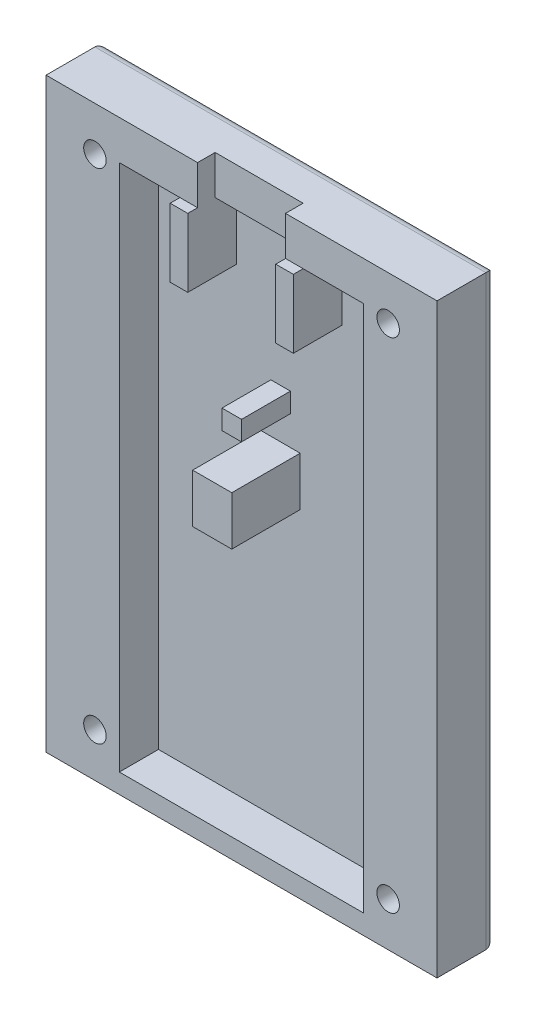
SolidWorks part; units mm, degrees
ref_plane "Front Plane" through (0, 0, 0) normal (1, 0, 0) x (0, 1, 0)
ref_plane "Top Plane" through (0, 0, 0) normal (0, 0, 1) x (0, 1, 0)
ref_plane "Right Plane" through (0, 0, 0) normal (0, 1, 0) x (-1, 0, 0)
sketch "Sketch1" plane through (0, 0, 0) normal (0, 0, 1) x (0, 1, 0)
  line L0 (0, -20) -> (60, -20) construction
  line L1 (0, 0) -> (60, 0)
  line L2 (0, 0) -> (0, -40)
  line L3 (0, -40) -> (60, -40)
  line L4 (60, 0) -> (60, -40)
  dimension "D1" = 60
  dimension "D2" = 40
extrude "Boss-Extrude1" add sketch "Sketch1" along normal blind 6
sketch "Sketch3" plane through (0, 0, 6) normal (0, 0, 1) x (1, 0, 0)
  line L0 (0, 55.5) -> (40, 55.5) construction
  line L1 (0, 60) -> (0, 0) construction
  line L2 (40, 0) -> (40, 60) construction
  line L3 (0, 4.5) -> (40, 4.5) construction
  line L4 (0, 30) -> (40, 30) construction
  line L5 (20, 60) -> (20, 0) construction
  line L6 (40, 60) -> (0, 60) construction
  line L7 (0, 0) -> (40, 0) construction
  circle A0 centre (5, 4.5) radius 1.15
  circle A1 centre (35, 4.5) radius 1.15
  circle A2 centre (5, 55.5) radius 1.15
  circle A3 centre (35, 55.5) radius 1.15
  dimension "D5" = 2.3
  dimension "D6" = 2.3
  dimension "D7" = 2.3
  dimension "D8" = 2.3
  dimension "D1" = 25.5
  dimension "D2" = 25.5
  dimension "D3" = 15
  dimension "D4" = 15
  dimension "D9" = 15
  dimension "D10" = 15
extrude "Cut-Extrude2" cut sketch "Sketch3" against normal through all
sketch "Sketch12" plane through (0, 0, 6) normal (0, 0, 1) x (1, 0, 0)
  line L0 (20, 60) -> (20, 0) construction
  line L1 (40, 60) -> (0, 60) construction
  line L2 (0, 0) -> (40, 0) construction
  line L4 (32.5, 56) -> (7.5, 56)
  line L5 (32.5, 56) -> (32.5, 2)
  line L6 (32.5, 2) -> (7.5, 2)
  line L7 (7.5, 56) -> (7.5, 2)
  line L8 (32.5, 56) -> (7.5, 2) construction
  line L9 (32.5, 2) -> (7.5, 56) construction
  point P6 (20, 29)
  dimension "D1" = 2
  dimension "D2" = 25
  dimension "D3" = 4
extrude "Cut-Extrude10" cut sketch "Sketch12" against normal blind 4
sketch "Sketch13" plane through (0, 0, 0) normal (0, 0, -1) x (1, 0, 0)
  line L0 (5, -4.5) -> (35, -4.5) construction
  line L1 (5, -55.5) -> (35, -55.5) construction
  line L3 (7.4249, -55.5) -> (6.2124, -53.4)
  line L4 (6.2124, -53.4) -> (3.7876, -53.4)
  line L5 (3.7876, -53.4) -> (2.5751, -55.5)
  line L6 (2.5751, -55.5) -> (3.7876, -57.6)
  line L7 (3.7876, -57.6) -> (6.2124, -57.6)
  line L8 (6.2124, -57.6) -> (7.4249, -55.5)
  line L9 (32.5751, -55.5) -> (33.7876, -57.6)
  line L10 (33.7876, -57.6) -> (36.2124, -57.6)
  line L11 (36.2124, -57.6) -> (37.4249, -55.5)
  line L12 (37.4249, -55.5) -> (36.2124, -53.4)
  line L13 (36.2124, -53.4) -> (33.7876, -53.4)
  line L14 (33.7876, -53.4) -> (32.5751, -55.5)
  line L15 (7.4249, -4.5) -> (6.2124, -2.4)
  line L16 (6.2124, -2.4) -> (3.7876, -2.4)
  line L17 (3.7876, -2.4) -> (2.5751, -4.5)
  line L18 (2.5751, -4.5) -> (3.7876, -6.6)
  line L19 (3.7876, -6.6) -> (6.2124, -6.6)
  line L20 (6.2124, -6.6) -> (7.4249, -4.5)
  line L21 (32.5751, -4.5) -> (33.7876, -6.6)
  line L22 (33.7876, -6.6) -> (36.2124, -6.6)
  line L23 (36.2124, -6.6) -> (37.4249, -4.5)
  line L24 (37.4249, -4.5) -> (36.2124, -2.4)
  line L25 (36.2124, -2.4) -> (33.7876, -2.4)
  line L26 (33.7876, -2.4) -> (32.5751, -4.5)
  circle A0 centre (5, -55.5) radius 2.1 construction
  circle A1 centre (35, -55.5) radius 2.1 construction
  circle A2 centre (5, -4.5) radius 2.1 construction
  circle A3 centre (35, -4.5) radius 2.1 construction
  dimension "D1" = 4.2
  dimension "D2" = 4.2
  dimension "D3" = 4.2
  dimension "D4" = 4.2
extrude "Cut-Extrude11" cut sketch "Sketch13" against normal blind 2.8
fillet "Fillet1" radius 1 4 edges at (40, 30, 0) (20, 0, 0) (0, 30, 0) (20, 60, 0)
sketch "Sketch15" plane through (0, 0, 6) normal (0, 0, 1) x (1, 0, 0)
  line L0 (20, 60) -> (20, 56) construction
  line L1 (40, 60) -> (0, 60) construction
  line L2 (32.5, 56) -> (7.5, 56) construction
  line L3 (32.5, 56) -> (7.5, 56) construction
  line L4 (24.5, 56) -> (15.5, 56)
  line L5 (24.5, 56) -> (24.5, 60)
  line L6 (24.5, 60) -> (15.5, 60)
  line L7 (15.5, 56) -> (15.5, 60)
  line L8 (24.5, 56) -> (15.5, 60) construction
  line L9 (24.5, 60) -> (15.5, 56) construction
  point P6 (20, 58)
  dimension "D1" = 9
extrude "Cut-Extrude13" cut sketch "Sketch15" against normal blind 1.8
sketch "Sketch16" plane through (0, 0, 2) normal (0, 0, 1) x (1, 0, 0)
  line L0 (20, 56) -> (20, 2) construction
  line L1 (32.5, 56) -> (7.5, 56) construction
  line L2 (7.5, 2) -> (32.5, 2) construction
  line L3 (18, 30.5) -> (18, 35.5)
  line L4 (18, 30.5) -> (22, 30.5)
  line L5 (18, 35.5) -> (22, 35.5)
  line L6 (22, 30.5) -> (22, 35.5)
  line L7 (18, 30.5) -> (22, 35.5) construction
  line L8 (18, 35.5) -> (22, 30.5) construction
  line L9 (0, 0) -> (40, 0) construction
  point P7 (20, 33)
  point P9 (20, 35.5)
  point P14 (22, 33)
  dimension "D1" = 35.5
  dimension "D2" = 5
  dimension "D3" = 4
extrude "Boss-Extrude2" add sketch "Sketch16" along normal blind 7
sketch "Sketch17" plane through (0, 0, 2) normal (0, 0, 1) x (1, 0, 0)
  line L0 (20, 56) -> (20, 35.5) construction
  line L1 (15.5, 56) -> (24.5, 56) construction
  line L2 (22, 35.5) -> (18, 35.5) construction
  line L3 (21, 38.5) -> (21, 40.5)
  line L4 (21, 38.5) -> (19, 38.5)
  line L5 (21, 40.5) -> (19, 40.5)
  line L6 (19, 38.5) -> (19, 40.5)
  line L7 (21, 38.5) -> (19, 40.5) construction
  line L8 (21, 40.5) -> (19, 38.5) construction
  line L10 (15.5, 56) -> (13.7, 56)
  line L11 (15.5, 56) -> (15.5, 49)
  line L12 (15.5, 49) -> (13.7, 49)
  line L13 (13.7, 56) -> (13.7, 49)
  line L14 (24.5, 56) -> (26.3, 56)
  line L15 (24.5, 56) -> (24.5, 49)
  line L16 (24.5, 49) -> (26.3, 49)
  line L17 (26.3, 56) -> (26.3, 49)
  line L18 (15.5, 60) -> (0, 60) construction
  point P7 (20, 39.5)
  point P8 (19, 39.5)
  dimension "D1" = 4
  dimension "D2" = 2
  dimension "D3" = 2
  dimension "D4" = 1.8
  dimension "D5" = 1.8
  dimension "D6" = 11
extrude "Boss-Extrude3" add sketch "Sketch17" along normal blind 5
